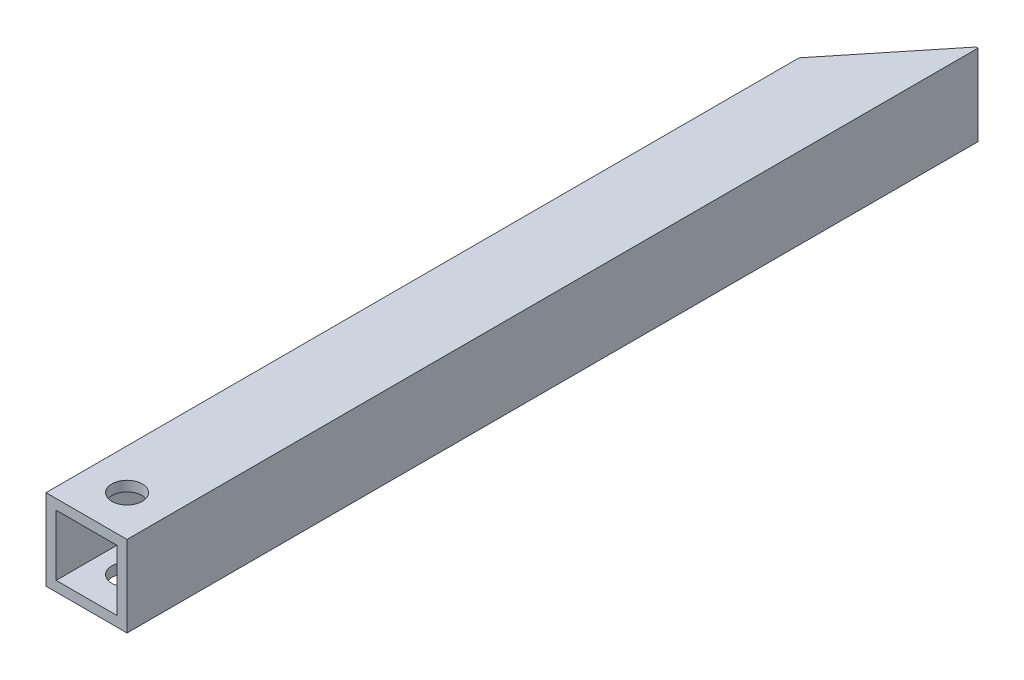
SolidWorks part; units mm, degrees
ref_plane "Front Plane" through (0, 0, 0) normal (0, 0, 1) x (1, 0, 0)
ref_plane "Top Plane" through (0, 0, 0) normal (0, 1, 0) x (1, 0, 0)
ref_plane "Right Plane" through (0, 0, 0) normal (1, 0, 0) x (0, 0, -1)
sketch "Sketch1" plane through (0, 0, 0) normal (0, 0, 1) x (1, 0, 0)
  line L0 (3.175, 22.225) -> (22.225, 22.225)
  line L1 (0, 0) -> (25.4, 0)
  line L2 (0, 0) -> (0, 25.4)
  line L3 (0, 25.4) -> (25.4, 25.4)
  line L4 (25.4, 0) -> (25.4, 25.4)
  line L5 (0, 0) -> (25.4, 25.4) construction
  line L6 (0, 25.4) -> (25.4, 0) construction
  line L7 (22.225, 3.175) -> (22.225, 22.225)
  line L8 (3.175, 3.175) -> (22.225, 3.175)
  line L9 (3.175, 3.175) -> (3.175, 22.225)
  point P4 (12.7, 12.7)
  dimension "D1" = 25.4
  dimension "D2" = 3.175
extrude "Boss-Extrude1" add sketch "Sketch1" along normal blind 266.7
sketch "Sketch2" plane through (0, 25.4, 0) normal (0, 1, 0) x (1, 0, 0)
  line L0 (28.2186, 4.253) -> (-38.6432, -78.4778) construction
  line L1 (28.2186, 4.253) -> (-38.6432, -78.4778)
  line L2 (28.2186, 4.253) -> (-14.4674, 75.011)
  line L3 (-14.4674, 75.011) -> (-121.8526, 10.229)
  line L4 (-121.8526, 10.229) -> (-38.6432, -78.4778)
extrude "Cut-Extrude1" cut sketch "Sketch2" against normal through all
sketch "Sketch3" plane through (0, 25.4, 0) normal (0, 1, 0) x (1, 0, 0)
  line L0 (12.7, -266.7) -> (12.7, -254) construction
  line L1 (25.4, -266.7) -> (0, -266.7) construction
  circle A0 centre (12.7, -254) radius 4.7625
  dimension "D2" = 9.525
  dimension "D1" = 12.7
extrude "Cut-Extrude2" cut sketch "Sketch3" against normal through all
